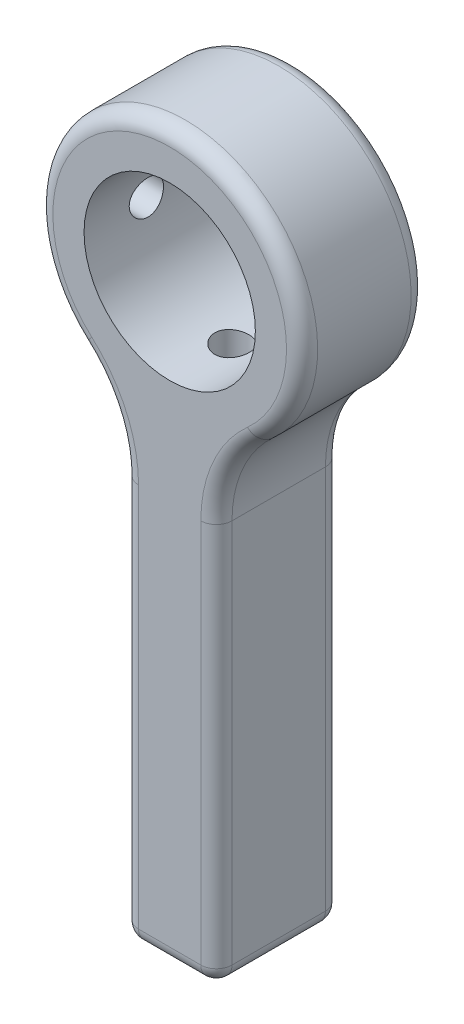
SolidWorks part; units mm, degrees
ref_plane "Front Plane" through (0, 0, 0) normal (0, 0, 1) x (1, 0, 0)
ref_plane "Top Plane" through (0, 0, 0) normal (0, 1, 0) x (1, 0, 0)
ref_plane "Right Plane" through (0, 0, 0) normal (1, 0, 0) x (0, 0, -1)
sketch "Sketch1" plane through (0, 0, 0) normal (0, 0, 1) x (1, 0, 0)
  line L0 (-4, 3) -> (-4, -3)
  line L1 (-3, -4) -> (3, -4)
  line L2 (55, 0) -> (-55, 0) construction
  line L3 (0, -55) -> (0, 55) construction
  arc A0 (-4, 3) -> (3, -4) centre (0, 0) cw
  arc A1 (-3, -4) -> (-4, -3) centre (0, 0) cw
  point P4 (-4, 0)
  point P7 (0, -4)
  dimension "D3" = 5
  dimension "D1" = 6
  dimension "D2" = 6
sketch "Sketch2" plane through (0, 0, 0) normal (0, 0, 1) x (1, 0, 0)
  line L0 (0, 0) -> (0, -38) construction
  line L1 (0, -38) -> (3, -38)
  line L2 (3, -38) -> (3, -7.953)
  line L3 (0, -38) -> (-3, -38)
  line L4 (-3, -38) -> (-3, -7.953)
  circle A0 centre (0, 0) radius 5.5
  arc A2 (-3, -7.953) -> (3, -7.953) centre (0, 0) cw
  dimension "D1" = 11
  dimension "D2" = 3
  dimension "D4" = 8.5
  dimension "D3" = 3
  dimension "D5" = 38
extrude "Boss-Extrude1" add sketch "Sketch2" along normal blind 8
sketch "Sketch3" plane through (0, 0, 0) normal (0, 1, 0) x (1, 0, 0)
  circle A0 centre (0, -4) radius 1.1
  dimension "D1" = 2.2
  dimension "D2" = 4
extrude "Cut-Extrude1" cut sketch "Sketch3" against normal through all
sketch "Sketch5" plane through (0, 0, 0) normal (0, 1, 0) x (1, 0, 0)
  circle A0 centre (0, -4) radius 1.75
  dimension "D1" = 3.5
extrude "Cut-Extrude2" cut sketch "Sketch5" against normal blind 88 from offset 8 offset against normal yes
sketch "Sketch6" plane through (0, 0, 0) normal (1, 0, 0) x (0, 0, -1)
  circle A0 centre (-4, 0) radius 1.1
  dimension "D1" = 4
  dimension "D2" = 2.2
extrude "Cut-Extrude3" cut sketch "Sketch6" against normal through all
fillet "Fillet2" radius 8 2 edges at (3, -7.953, 4) (-3, -7.953, 4)
fillet "Fillet1" radius 1 14 edges at (-3, -25.1492, 0) (0, -38, 0) (3, -25.1492, 0) (0, 8.5, 0) (3, -25.1492, 8) (0, -38, 8) (-3, -25.1492, 8) (0, 8.5, 8) (3, -38, 4) (-3, -38, 4) (-3.697, -9.0324, 0) (3.697, -9.0324, 0) (-3.697, -9.0324, 8) (3.697, -9.0324, 8)
